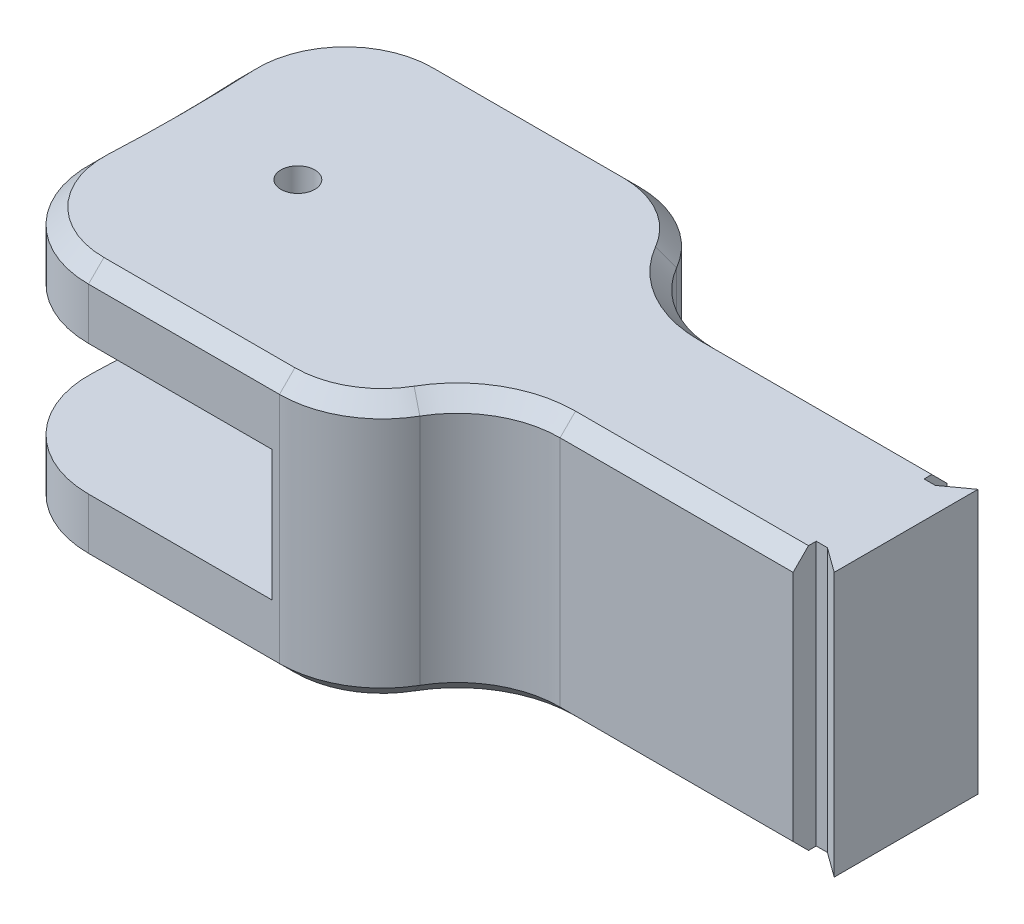
SolidWorks part; units mm, degrees
ref_plane "Front Plane" through (0, 0, 0) normal (0, 0, 1) x (1, 0, 0)
ref_plane "Top Plane" through (0, 0, 0) normal (0, 1, 0) x (1, 0, 0)
ref_plane "Right Plane" through (0, 0, 0) normal (1, 0, 0) x (0, 0, -1)
sketch "Sketch1" plane through (0, 0, 0) normal (0, 0, 1) x (1, 0, 0)
  line L0 (0, 0) -> (28.575, 0)
  line L1 (28.575, 0) -> (28.575, 12.7)
  line L2 (28.575, 12.7) -> (0, 12.7)
  line L3 (0, 12.7) -> (0, 19.2)
  line L4 (0, 19.2) -> (38.575, 19.2)
  line L5 (38.575, 19.2) -> (38.575, -6.5)
  line L6 (38.575, -6.5) -> (0, -6.5)
  line L7 (0, -6.5) -> (0, 0)
  line L8 (0, 19.2) -> (-144.7872, 19.2) construction
  line L9 (-144.7872, 19.2) -> (-144.7872, -6.5) construction
  line L10 (-144.7872, -6.5) -> (0, -6.5) construction
  dimension "D1" = 12.7
  dimension "D2" = 6.5
  dimension "D3" = 10
  dimension "D4" = 28.575
  dimension "D5" = 346.7243
revolve "Revolve1" add sketch "Sketch1" angle 360 about L9
sketch "Sketch2" plane through (0, 19.2, 0) normal (0, 1, 0) x (1, 0, 0)
  line L1 (-1.0615, 17.5) -> (38.575, 17.5)
  line L2 (-1.0615, 17.5) -> (-1.0615, -17.5)
  line L3 (-1.0615, -17.5) -> (38.575, -17.5)
  line L4 (38.575, 17.5) -> (38.575, -17.5)
  line L5 (18.7568, -17.5) -> (18.7568, 17.5) construction
  line L6 (-1.0615, 0) -> (38.575, 0) construction
  circle A0 centre (-144.7872, 0) radius 144.7872 construction
  circle A1 centre (-144.7872, 0) radius 183.3622 construction
  point P6 (54.45, 0)
  point P9 (-0.9052, -15.2502)
  point P240 (18.7568, 0)
  dimension "D1" = 35
extrude "Cut-Extrude1" cut sketch "Sketch2" against normal through all flip side to cut
sketch "Sketch3" plane through (0, 19.2, 0) normal (0, 1, 0) x (1, 0, 0)
  line L0 (0, 0) -> (68.4216, 0) construction
  line L1 (38.4216, 7.5) -> (68.4216, 7.5)
  line L2 (68.4216, 7.5) -> (68.4216, -7.5)
  line L3 (68.4216, -7.5) -> (38.4216, -7.5)
  arc A0 (37.738, -17.5) -> (37.738, 17.5) centre (-144.7872, 0) ccw construction
  arc A1 (38.4216, -7.5) -> (38.4216, 7.5) centre (-144.7872, 0) ccw
  point P8 (0, 0)
  dimension "D1" = 30
  dimension "D2" = 15
extrude "Boss-Extrude1" add sketch "Sketch3" against normal through all
sketch "Sketch4" plane through (0, 19.2, 0) normal (0, 1, 0) x (1, 0, 0)
  line L0 (68.4216, 0) -> (71.9216, 0) construction
  line L1 (68.4216, -7.5) -> (68.4216, 7.5) construction
  line L3 (71.9216, 7) -> (71.9216, -7)
  line L5 (68.4216, 5.25) -> (68.4216, -5.25)
  line L6 (68.4216, 5.25) -> (69.5116, 5.25)
  line L7 (69.5116, 5.25) -> (71.9216, 7)
  line L8 (68.4216, -5.25) -> (69.5116, -5.25)
  line L9 (69.5116, -5.25) -> (71.9216, -7)
  point P6 (85.5437, 3.8837)
  point P11 (87.7966, 6.4032)
  dimension "D1" = 3.5
  dimension "D2" = 2.41
  dimension "D3" = 14
  dimension "D4" = 10.5
extrude "Boss-Extrude2" add sketch "Sketch4" against normal through all
fillet "Fillet1" radius 10 6 edges at (-1.0615, 15.95, -17.5) (-1.0615, -3.25, -17.5) (-1.0615, -3.25, 17.5) (-1.0615, 15.95, 17.5) (37.738, 6.35, -17.5) (37.738, 6.35, 17.5)
hole_wizard "M4x0.7 Tapped Hole1" positions "Sketch5" profile "Sketch6" tap size "M4x0.7" standard "ANSI Metric" end condition through all
sketch "Sketch5" plane through (0, 19.2, 0) normal (0, 1, 0) x (1, 0, 0)
  line L0 (0, 0) -> (12.7, 0) construction
  arc A0 (-0.1701, -7.0155) -> (-0.1701, 7.0155) centre (-144.7872, 0) ccw construction
  point P0 (12.7, 0)
  dimension "D1" = 12.7
sketch "Sketch6" plane through (12.7, 19.2, 0) normal (1, 0, 0) x (0, 0, 1)
  line L0 (0, 0) -> (0, 25.7)
  line L1 (0, 25.7) -> (1.65, 25.7)
  line L2 (1.65, 25.7) -> (1.65, 0)
  line L5 (1.65, 0) -> (0, 0)
  line L11 (0, -6.35) -> (0, 107.95) construction
  dimension "Thru Tap Drill Dia." = 3.3
  dimension "Thru Tap Drill Depth" = 25.7
cosmetic thread "Hole Thread1" parameters "D2"=4
fillet "Fillet2" radius 10 2 edges at (38.4216, 6.35, 7.5) (38.4216, 6.35, -7.5)
chamfer "Chamfer1" distance 1.5 angle 45 22 edges at (19.1154, 19.2, 17.5) (2.5778, 19.2, 14.3976) (2.5778, 19.2, -14.3976) (33.4127, 19.2, 16.1603) (33.4127, -6.5, 16.1603) (57.0774, 19.2, 7.5) (57.0774, -6.5, 7.5) (33.4127, 19.2, -16.1603) (40.7332, 19.2, 8.8397) (40.7332, -6.5, 8.8397) (40.7332, 19.2, -8.8397) (40.7332, -6.5, -8.8397) (57.0774, -6.5, -7.5) (57.0774, 19.2, -7.5) (19.1154, 19.2, -17.5) (19.1154, -6.5, -17.5) (19.1154, -6.5, 17.5) (0, -6.5, 0) (2.5778, -6.5, 14.3976) (2.5778, -6.5, -14.3976) (33.4127, -6.5, -16.1603) (0, 19.2, 0)
